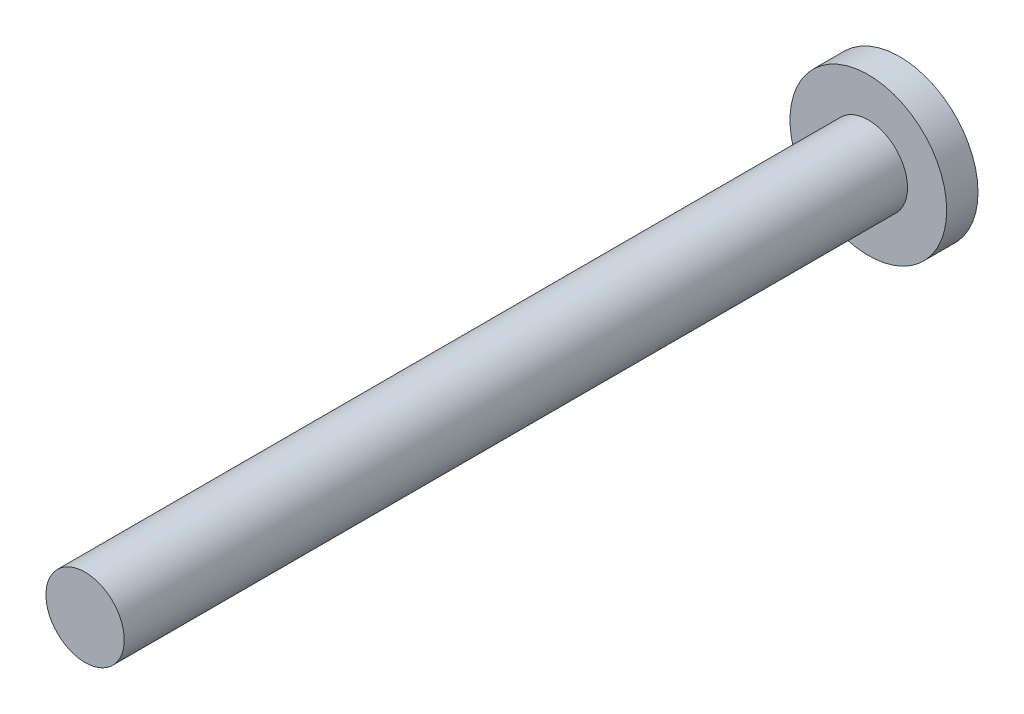
SolidWorks part; units mm, degrees
ref_plane "Front Plane" through (0, 0, 0) normal (0, 0, 1) x (1, 0, 0)
ref_plane "Top Plane" through (0, 0, 0) normal (0, 1, 0) x (1, 0, 0)
ref_plane "Right Plane" through (0, 0, 0) normal (1, 0, 0) x (0, 0, -1)
sketch "Sketch1" plane through (0, 0, 0) normal (0, 1, 0) x (1, 0, 0)
  line L0 (0, 0) -> (0, 52)
  line L1 (0, 52) -> (5, 52)
  line L2 (5, 52) -> (5, 50)
  line L3 (5, 50) -> (2.5, 50)
  line L4 (2.5, 50) -> (2.5, 0)
  line L5 (2.5, 0) -> (0, 0)
  dimension "D1" = 50
  dimension "D2" = 2
  dimension "D3" = 2.5
  dimension "D4" = 5
revolve "Revolve1" add sketch "Sketch1" angle 360 about L0
